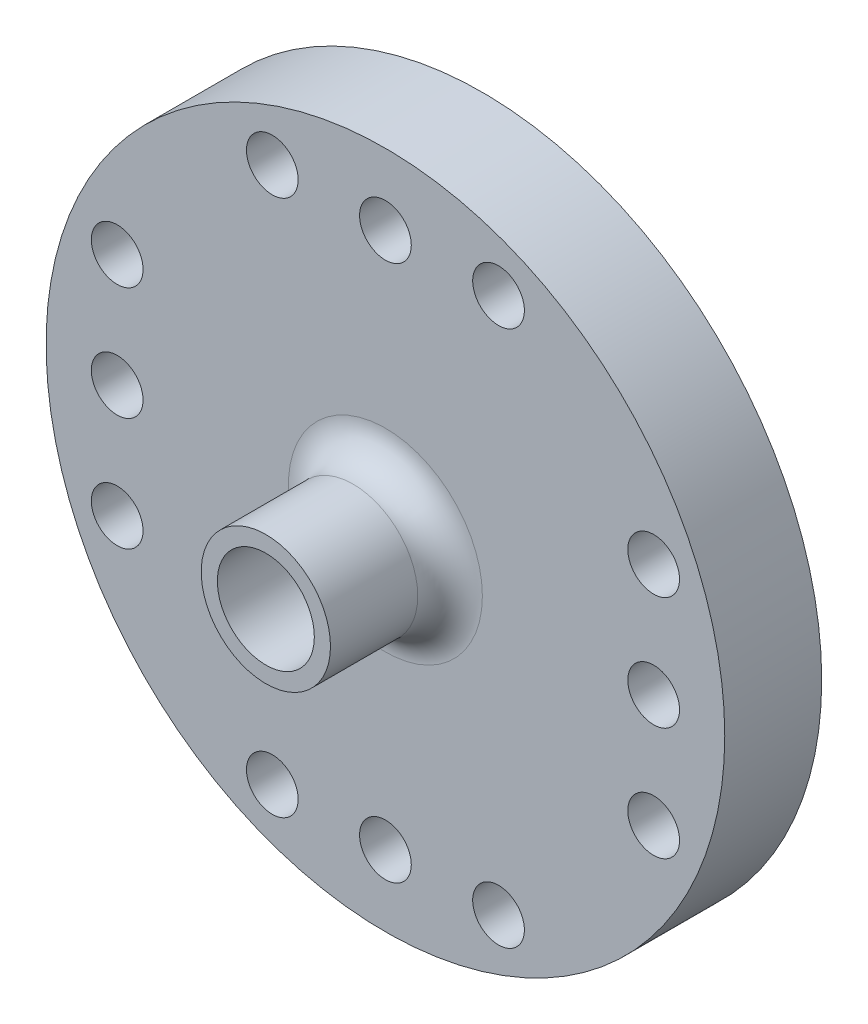
SolidWorks part; units mm, degrees
ref_plane "Plan de face" through (0, 0, 0) normal (0, 0, 1) x (1, 0, 0)
ref_plane "Plan de dessus" through (0, 0, 0) normal (0, 1, 0) x (1, 0, 0)
ref_plane "Plan de droite" through (0, 0, 0) normal (1, 0, 0) x (0, 0, -1)
sketch "Esquisse1" plane through (0, 0, 0) normal (0, 0, 1) x (1, 0, 0)
  line L1 (-7.2702, 1.0347) -> (-23.8702, 1.0347) construction
  line L2 (-7.2702, 1.0347) -> (-7.2702, 8.0347) construction
  line L3 (-7.2702, -3.7653) -> (-23.8702, -3.7653) construction
  line L4 (-7.2702, -3.7653) -> (-7.2702, 12.8347) construction
  line L5 (-7.2702, 12.8347) -> (-23.8702, 12.8347) construction
  line L6 (-23.8702, -3.7653) -> (-23.8702, 12.8347) construction
  line L7 (-7.2702, -3.7653) -> (-23.8702, 12.8347) construction
  line L8 (-7.2702, 12.8347) -> (-23.8702, -3.7653) construction
  line L9 (-12.0702, -3.7653) -> (-19.0702, -3.7653) construction
  line L10 (-12.0702, -3.7653) -> (-12.0702, 12.8347) construction
  line L11 (-12.0702, 12.8347) -> (-19.0702, 12.8347) construction
  line L12 (-19.0702, -3.7653) -> (-19.0702, 12.8347) construction
  line L13 (-12.0702, -3.7653) -> (-19.0702, 12.8347) construction
  line L14 (-12.0702, 12.8347) -> (-19.0702, -3.7653) construction
  line L15 (-7.2702, 8.0347) -> (-23.8702, 8.0347) construction
  line L16 (-23.8702, 1.0347) -> (-23.8702, 8.0347)
  line L17 (-7.2702, 1.0347) -> (-23.8702, 8.0347) construction
  line L18 (-7.2702, 8.0347) -> (-23.8702, 1.0347) construction
  circle A0 centre (-12.0702, 12.8347) radius 0.8
  circle A1 centre (-15.5702, 4.5347) radius 10.5
  circle A2 centre (-15.5702, 4.5347) radius 1.5
  circle A3 centre (-7.2702, 4.5347) radius 0.8
  circle A4 centre (-15.5702, 12.8347) radius 0.8
  circle A5 centre (-23.8702, 4.5347) radius 0.8
  circle A6 centre (-15.5702, -3.7653) radius 0.8
  circle A7 centre (-19.0702, 12.8347) radius 0.8
  circle A8 centre (-19.0702, -3.7653) radius 0.8
  circle A9 centre (-12.0702, -3.7653) radius 0.8
  circle A10 centre (-7.2702, 8.0347) radius 0.8
  circle A11 centre (-7.2702, 1.0347) radius 0.8
  circle A12 centre (-23.8702, 1.0347) radius 0.8
  circle A13 centre (-23.8702, 8.0347) radius 0.8
  dimension "D1" = 7
  dimension "D2" = 21
  dimension "D3" = 3
  dimension "D4" = 16.6
  dimension "D5" = 1.6
extrude "Boss.-Extru.1" add sketch "Esquisse1" along normal blind 3
sketch "Esquisse3" plane through (0, 0, 3) normal (0, 0, 1) x (1, 0, 0)
  circle A0 centre (-15.5702, 4.5347) radius 2
  circle A1 centre (-15.5702, 4.5347) radius 1.5
  dimension "D1" = 4
  dimension "D2" = 3
extrude "Boss.-Extru.2" add sketch "Esquisse3" along normal blind 3.7
fillet "Congé1" radius 1 1 edges at (-13.5702, 4.5347, 3)
